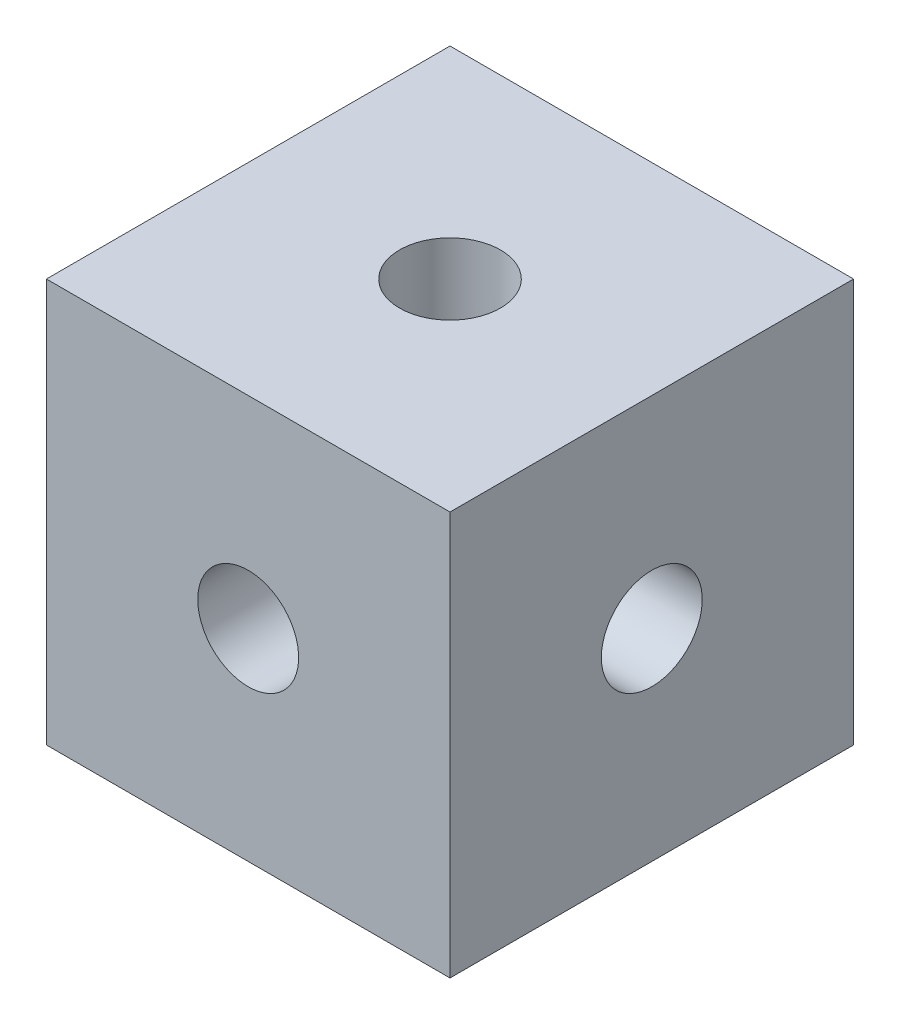
SolidWorks part; units mm, degrees
ref_plane "Front Plane" through (0, 0, 0) normal (0, 0, 1) x (1, 0, 0)
ref_plane "Top Plane" through (0, 0, 0) normal (0, 1, 0) x (1, 0, 0)
ref_plane "Right Plane" through (0, 0, 0) normal (1, 0, 0) x (0, 0, -1)
sketch "Sketch1" plane through (0, 0, 0) normal (0, 0, 1) x (1, 0, 0)
  line L1 (-12.7, -12.7) -> (12.7, -12.7)
  line L2 (-12.7, -12.7) -> (-12.7, 12.7)
  line L3 (-12.7, 12.7) -> (12.7, 12.7)
  line L4 (12.7, -12.7) -> (12.7, 12.7)
  line L5 (-12.7, -12.7) -> (12.7, 12.7) construction
  line L6 (-12.7, 12.7) -> (12.7, -12.7) construction
  point P0 (0, 0)
  dimension "D1" = 25.4
extrude "Boss-Extrude1" add sketch "Sketch1" along normal blind 25.4
hole_wizard "1/4 (0.25) Diameter Hole1" positions "Sketch2" profile "Sketch3" hole size "1/4" standard "ANSI Inch" end condition through all
sketch "Sketch2" plane through (0, 0, 0) normal (0, 0, -1) x (-1, 0, 0)
  point P6 (0, 0)
sketch "Sketch3" plane through (0, 0, 0) normal (1, 0, 0) x (0, 1, 0)
  line L0 (0, 0) -> (0, 25.4)
  line L1 (0, 25.4) -> (3.175, 25.4)
  line L2 (3.175, 25.4) -> (3.175, 0)
  line L5 (3.175, 0) -> (0, 0)
  line L11 (0, -6.35) -> (0, 107.95) construction
  dimension "Thru Hole Dia." = 6.35
  dimension "Thru Hole Depth" = 25.4
hole_wizard "1/4 (0.25) Diameter Hole2" positions "Sketch4" profile "Sketch5" hole size "1/4" standard "ANSI Inch" end condition through all
sketch "Sketch4" plane through (0, 12.7, 0) normal (0, 1, 0) x (1, 0, 0)
  line L0 (12.7, -25.4) -> (-12.7, 0) construction
  point P7 (0, -12.7)
sketch "Sketch5" plane through (0, 12.7, 12.7) normal (1, 0, 0) x (0, 0, 1)
  line L0 (0, 0) -> (0, 25.4)
  line L1 (0, 25.4) -> (3.175, 25.4)
  line L2 (3.175, 25.4) -> (3.175, 0)
  line L5 (3.175, 0) -> (0, 0)
  line L11 (0, -6.35) -> (0, 107.95) construction
  dimension "Thru Hole Dia." = 6.35
  dimension "Thru Hole Depth" = 25.4
hole_wizard "1/4 (0.25) Diameter Hole3" positions "Sketch6" profile "Sketch7" hole size "1/4" standard "ANSI Inch" end condition through all
sketch "Sketch6" plane through (-12.7, 0, 0) normal (-1, 0, 0) x (0, 0, 1)
  line L1 (25.4, -12.7) -> (0, 12.7) construction
  point P7 (12.7, 0)
sketch "Sketch7" plane through (-12.7, 0, 12.7) normal (0, 1, 0) x (0, 0, 1)
  line L0 (0, 0) -> (0, 25.4)
  line L1 (0, 25.4) -> (3.175, 25.4)
  line L2 (3.175, 25.4) -> (3.175, 0)
  line L5 (3.175, 0) -> (0, 0)
  line L11 (0, -6.35) -> (0, 107.95) construction
  dimension "Thru Hole Dia." = 6.35
  dimension "Thru Hole Depth" = 25.4
